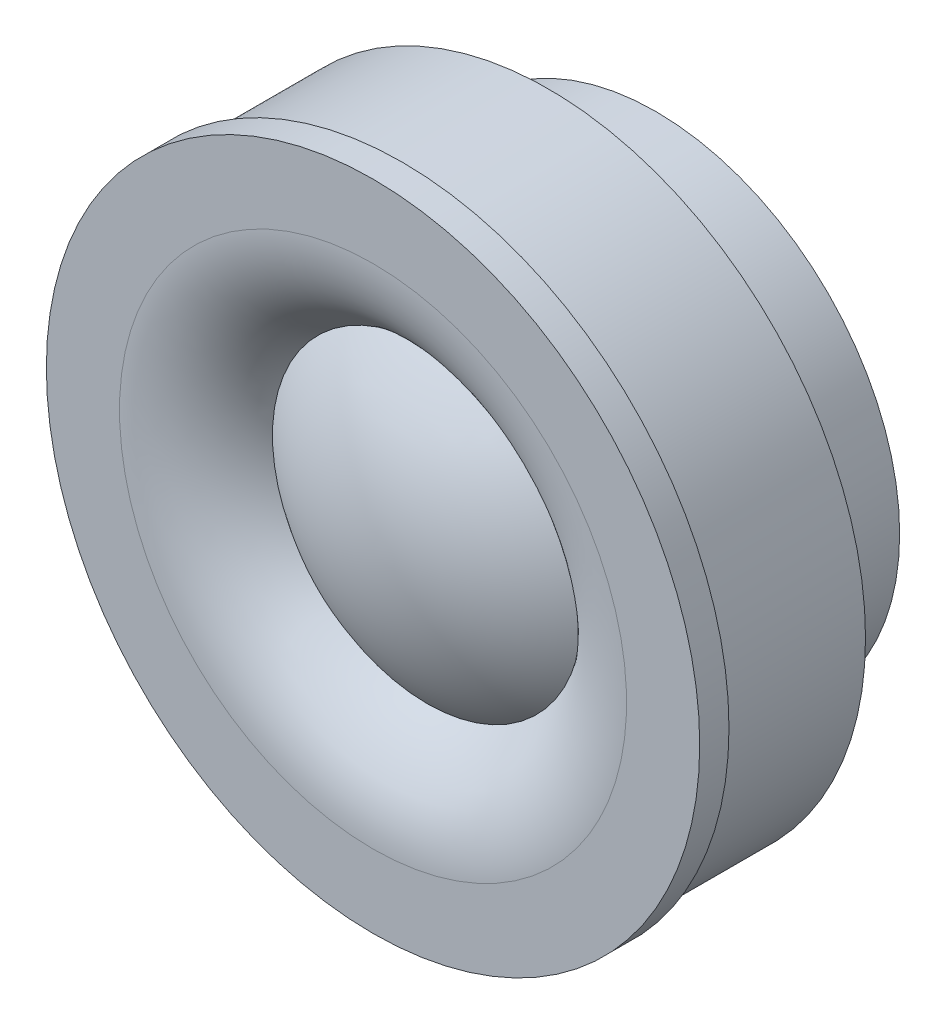
SolidWorks part; units mm, degrees
ref_plane "Front Plane" through (0, 0, 0) normal (0, 0, 1) x (1, 0, 0)
ref_plane "Top Plane" through (0, 0, 0) normal (0, 1, 0) x (1, 0, 0)
ref_plane "Right Plane" through (0, 0, 0) normal (1, 0, 0) x (0, 0, -1)
sketch "Sketch1" plane through (0, 0, 0) normal (0, 0, 1) x (1, 0, 0)
  circle A0 centre (0, 0) radius 16.25
  dimension "D1" = 32.5
extrude "Boss-Extrude1" add sketch "Sketch1" against normal blind 9
sketch "Sketch2" plane through (0, 0, -9) normal (0, 0, -1) x (-1, 0, 0)
  circle A0 centre (0, 0) radius 12.5
  dimension "D1" = 25
extrude "Boss-Extrude3" add sketch "Sketch2" along normal offset from surface (5.5 mm away) 14.5 up to face at (16.25, 0, 0)
sketch "Sketch3" plane through (0, 0, 0) normal (0, 0, 1) x (1, 0, 0)
  circle A0 centre (0, 0) radius 16.75
  circle A1 centre (0, 0) radius 16.25 construction
  dimension "D1" = 0.5
extrude "Boss-Extrude4" add sketch "Sketch3" against normal blind 1.5
sketch "Sketch5" plane through (0, 0, 0) normal (1, 0, 0) x (0, 0, -1)
  line L0 (0, 16.75) -> (0, -16.75) construction
  line L1 (0, 0) -> (20.2215, 0) construction
  line L2 (0, 0) -> (0, -6.7603) construction
  line L4 (0, 13) -> (-11.1979, 13)
  line L5 (-11.1979, 13) -> (-11.1979, 0)
  line L6 (-11.1979, 0) -> (0, 0)
  arc A0 (0, 13) -> (2.7796, 7.9375) centre (6, 13) ccw
  arc A1 (2.7796, 7.9375) -> (0, 0) centre (12.7231, 0) ccw
  dimension "D1" = 6
  dimension "D3" = 15.875
  dimension "D2" = 26
revolve "Cut-Revolve4" cut sketch "Sketch5" angle 360 about L6
